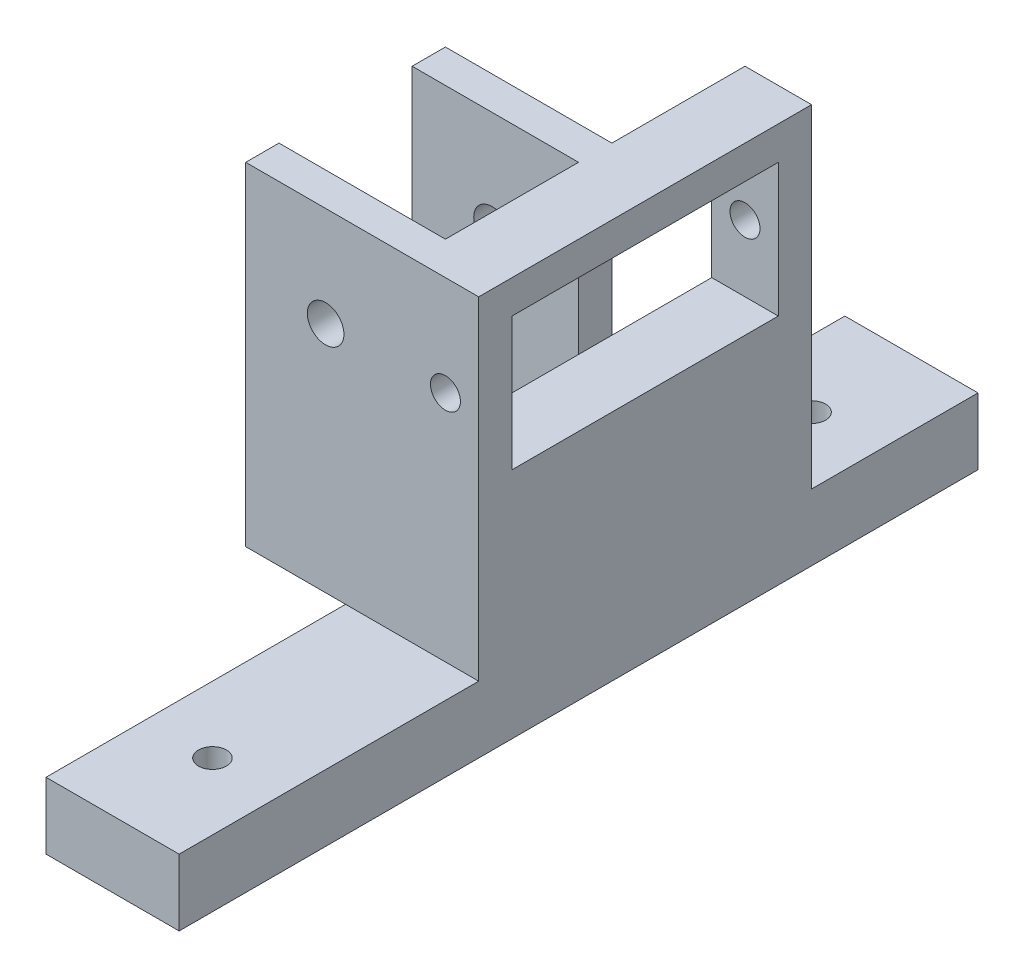
SolidWorks part; units mm, degrees
ref_plane "Front Plane" through (0, 0, 0) normal (0, 0, 1) x (1, 0, 0)
ref_plane "Top Plane" through (0, 0, 0) normal (0, 1, 0) x (1, 0, 0)
ref_plane "Right Plane" through (0, 0, 0) normal (1, 0, 0) x (0, 0, -1)
sketch "Sketch4" plane through (0, 0, 0) normal (0, 1, 0) x (1, 0, 0)
  line L1 (0, 0) -> (40, 0)
  line L2 (0, 0) -> (0, 80)
  line L3 (0, 80) -> (40, 80)
  line L4 (40, 0) -> (40, 80)
  dimension "D1" = 80
  dimension "D2" = 40
extrude "Boss-Extrude4" add sketch "Sketch4" along normal blind 5
sketch "Sketch5" plane through (0, 5, 0) normal (0, 1, 0) x (1, 0, 0)
  line L0 (40, 40) -> (30, 40)
  line L1 (30, 30) -> (30, 50) construction
  line L2 (40, 50) -> (30, 50)
  line L3 (30, 50) -> (30, 55)
  line L4 (0, 80) -> (0, 0)
  line L5 (0, 0) -> (40, 0)
  line L6 (40, 0) -> (40, 80)
  line L7 (40, 80) -> (0, 80)
  line L8 (0, 80) -> (0, 0)
  line L9 (0, 0) -> (40, 0)
  line L10 (40, 0) -> (40, 80)
  line L11 (40, 80) -> (0, 80)
  line L12 (30, 55) -> (40, 55)
  line L13 (40, 55) -> (40, 50)
  line L14 (40, 30) -> (30, 30)
  line L15 (30, 30) -> (30, 25)
  line L16 (30, 25) -> (40, 25)
  line L17 (40, 25) -> (40, 30)
  point P9 (30, 40)
  line M11 (40, 0) -> (40, 80)
  dimension "D2" = 10
  dimension "D3" = 10
  dimension "D4" = 5
  dimension "D5" = 5
  dimension "D1" = 0
extrude "Boss-Extrude6" add sketch "Sketch5" along normal blind 50 contours L12 L3 L2 M11 | L15 L16 L10 L14
sketch "Sketch7" plane through (0, 0, -50) normal (0, 0, 1) x (1, 0, 0)
  line L1 (30, 5) -> (40, 5)
  line L2 (30, 5) -> (30, 30)
  line L3 (30, 30) -> (40, 30)
  line L4 (40, 5) -> (40, 30)
  line L5 (40, 55) -> (40, 5) construction
  line L7 (30, 55) -> (40, 55)
  line L8 (30, 55) -> (30, 50)
  line L9 (30, 50) -> (40, 50)
  line L10 (40, 55) -> (40, 50)
  dimension "D1" = 25
  dimension "D2" = 10
  dimension "D3" = 5
extrude "Boss-Extrude7" add sketch "Sketch7" along normal up to surface (20 mm away) contours L8 L7 L10 L9 | L2 L1 L4 L3 up to face at (35, 30, -30)
sketch "Sketch9" plane through (0, 0, 0) normal (-1, 0, 0) x (0, 0, 1)
  line L4 (-80, 0) -> (0, 0)
  line L5 (0, 0) -> (0, 5)
  line L6 (0, 5) -> (-80, 5)
  line L7 (-80, 5) -> (-80, 0)
  line L8 (-80, 0) -> (0, 0)
  line L9 (0, 0) -> (0, 5)
  line L10 (0, 5) -> (-80, 5)
  line L12 (-80, 5) -> (-80, 0)
  dimension "D1" = 0
extrude "Boss-Extrude9" add sketch "Sketch9" along normal blind 10
sketch "Sketch10" plane through (0, 0, 0) normal (0, 0, 1) x (1, 0, 0)
  line L4 (-10, 0) -> (40, 0)
  line L5 (40, 0) -> (40, 5)
  line L6 (40, 5) -> (-10, 5)
  line L7 (-10, 5) -> (-10, 0)
  line L8 (-10, 0) -> (40, 0)
  line L9 (40, 0) -> (40, 5)
  line L10 (40, 5) -> (-10, 5)
  line L11 (-10, 5) -> (-10, 0)
  dimension "D1" = 0
extrude "Boss-Extrude10" add sketch "Sketch10" along normal blind 20
sketch "Sketch11" plane through (0, 0, -50) normal (0, 0, 1) x (1, 0, 0)
  line L0 (30, 40) -> (35, 40)
  line L4 (30, 30) -> (40, 30)
  line L5 (40, 30) -> (40, 50)
  line L6 (40, 50) -> (30, 50)
  line L7 (30, 50) -> (30, 30)
  line L8 (30, 30) -> (40, 30)
  line L9 (40, 30) -> (40, 50)
  line L10 (40, 50) -> (30, 50)
  line L11 (30, 50) -> (30, 30)
  circle A0 centre (35, 40) radius 2.25
  dimension "D3" = 4.5
  dimension "D2" = 5
  dimension "D1" = 0
extrude "Cut-Extrude1" cut sketch "Sketch11" against normal mid plane 50
sketch "Sketch12" plane through (0, 0, -25) normal (0, 0, 1) x (1, 0, 0)
  circle A0 centre (35, 40) radius 2.25 construction
  circle A1 centre (35, 40) radius 2.25
  circle A2 centre (35, 40) radius 4
  dimension "D1" = 8
extrude "Cut-Extrude2" cut sketch "Sketch12" against normal blind 2
sketch "Sketch15" plane through (30, 0, 0) normal (-1, 0, 0) x (0, 0, 1)
  line L1 (-55, 55) -> (-50, 55)
  line L2 (-55, 55) -> (-55, 5)
  line L3 (-55, 5) -> (-50, 5)
  line L4 (-50, 55) -> (-50, 5)
  line L5 (-25, 55) -> (-30, 55)
  line L6 (-25, 55) -> (-25, 5)
  line L7 (-25, 5) -> (-30, 5)
  line L8 (-30, 55) -> (-30, 5)
  dimension "D1" = 50
  dimension "D2" = 5
  dimension "D3" = 50
  dimension "D4" = 5
extrude "Boss-Extrude11" add sketch "Sketch15" along normal blind 20
sketch "Sketch16" plane through (0, 0, -25) normal (0, 0, 1) x (1, 0, 0)
  line L0 (35, 40) -> (17, 40)
  circle A0 centre (35, 40) radius 4 construction
  circle A1 centre (35, 40) radius 4
  circle A2 centre (17, 40) radius 2.75
  dimension "D2" = 5.5
  dimension "D1" = 18
extrude "Cut-Extrude4" cut sketch "Sketch16" against normal up to surface (30 mm away) up to face at (32.75, 40, -55)
sketch "Sketch19" plane through (10, 0, 0) normal (-1, 0, 0) x (0, 0, 1)
  line L4 (-55, 55) -> (-55, 5)
  line L5 (-55, 5) -> (-50, 5)
  line L6 (-50, 5) -> (-50, 55)
  line L7 (-50, 55) -> (-55, 55)
  line L8 (-55, 55) -> (-55, 5)
  line L10 (-50, 5) -> (-50, 55)
  line L11 (-50, 55) -> (-55, 55)
  line L12 (-25, 5) -> (-25, 55)
  line L13 (-25, 55) -> (-30, 55)
  line L14 (-30, 55) -> (-30, 5)
  line L15 (-30, 5) -> (-25, 5)
  line L16 (-25, 5) -> (-25, 55)
  line L17 (-25, 55) -> (-30, 55)
  line L18 (-30, 55) -> (-30, 5)
  line L20 (-55, 5) -> (-50, 5)
  line L21 (-30, 5) -> (-25, 5)
  dimension "D1" = 0
  dimension "D2" = 0
extrude "Boss-Extrude12" add sketch "Sketch19" along normal blind 5
sketch "Sketch21" plane through (0, 0, 0) normal (0, -1, 0) x (1, 0, 0)
  line L4 (40, -80) -> (40, 20)
  line L5 (40, 20) -> (-10, 20)
  line L6 (-10, 20) -> (-10, -80)
  line L7 (-10, -80) -> (40, -80)
  line L8 (40, -80) -> (40, 20)
  line L9 (40, 20) -> (-10, 20)
  line L10 (-10, 20) -> (-10, -80)
  line L11 (-10, -80) -> (40, -80)
  dimension "D1" = 0
extrude "Boss-Extrude14" add sketch "Sketch21" along normal blind 5
sketch "Sketch22" plane through (0, 0, -80) normal (0, 0, -1) x (-1, 0, 0)
  line L4 (-40, 5) -> (-40, -5)
  line L5 (-40, -5) -> (10, -5)
  line L6 (10, -5) -> (10, 5)
  line L7 (10, 5) -> (-40, 5)
  line L8 (-40, 5) -> (-40, -5)
  line L9 (-40, -5) -> (10, -5)
  line L10 (10, -5) -> (10, 5)
  line L11 (10, 5) -> (-40, 5)
  dimension "D1" = 0
extrude "Boss-Extrude15" add sketch "Sketch22" along normal blind 20
sketch "Sketch24" plane through (0, 55, 0) normal (0, 1, 0) x (1, 0, 0)
  line L1 (5, 55) -> (40, 55)
  line L2 (5, 55) -> (5, 50)
  line L3 (5, 50) -> (40, 50)
  line L4 (40, 55) -> (40, 50)
  line L5 (40, 25) -> (40, 55) construction
  dimension "D1" = 35
  dimension "D2" = 5
extrude "Cut-Extrude5" cut sketch "Sketch24" against normal blind 50
sketch "Sketch25" plane through (0, 0, -50) normal (0, 0, -1) x (-1, 0, 0)
  line L4 (-30, 5) -> (-30, 30)
  line L5 (-30, 30) -> (-40, 30)
  line L6 (-40, 30) -> (-40, 5)
  line L7 (-40, 5) -> (-30, 5)
  line L8 (-30, 5) -> (-30, 30)
  line L9 (-30, 30) -> (-40, 30)
  line L10 (-40, 30) -> (-40, 5)
  line L11 (-40, 5) -> (-30, 5)
  line L12 (-30, 50) -> (-30, 55)
  line L13 (-30, 55) -> (-40, 55)
  line L14 (-40, 55) -> (-40, 50)
  line L15 (-40, 50) -> (-30, 50)
  line L16 (-30, 50) -> (-30, 55)
  line L17 (-30, 55) -> (-40, 55)
  line L18 (-40, 55) -> (-40, 50)
  line L19 (-40, 50) -> (-30, 50)
  dimension "D1" = 0
  dimension "D2" = 0
extrude "Boss-Extrude16" add sketch "Sketch25" along normal blind 25
sketch "Sketch26" plane through (0, 30, 0) normal (0, 1, 0) x (1, 0, 0)
  line L1 (40, 75) -> (30, 75)
  line L2 (40, 75) -> (40, 70)
  line L3 (40, 70) -> (30, 70)
  line L4 (30, 75) -> (30, 70)
  line L5 (30, 30) -> (30, 75) construction
  dimension "D1" = 5
  dimension "D2" = 10
extrude "Boss-Extrude17" add sketch "Sketch26" along normal blind 20
sketch "Sketch27" plane through (0, 0, -27) normal (0, 0, 1) x (1, 0, 0)
  circle A0 centre (35, 40) radius 2.25 construction
  circle A1 centre (35, 40) radius 4
  circle A2 centre (35, 40) radius 4
  circle A3 centre (35, 40) radius 2.25
  dimension "D1" = 0
extrude "Boss-Extrude18" add sketch "Sketch27" along normal up to surface (2 mm away) up to face at (19.75, 40, -25)
sketch "Sketch28" plane through (0, 0, -25) normal (0, 0, 1) x (1, 0, 0)
  circle A0 centre (35, 40) radius 2.25 construction
  circle A1 centre (35, 40) radius 2.25
extrude "Cut-Extrude6" cut sketch "Sketch28" against normal blind 50
sketch "Sketch29" plane through (0, 5, 0) normal (0, 1, 0) x (1, 0, 0)
  line L0 (5, 30) -> (5, 50) construction
  line L2 (5, 50) -> (30, 50)
  line L3 (5, 50) -> (5, 55)
  line L4 (5, 55) -> (30, 55)
  line L5 (30, 50) -> (30, 55)
  line L6 (30, 30) -> (30, 75) construction
  dimension "D1" = 20
  dimension "D2" = 5
  dimension "D3" = 25
extrude "Boss-Extrude19" add sketch "Sketch29" along normal up to surface (50 mm away) contours L3 L2 L5 L4
sketch "Sketch31" plane through (0, 0, -25) normal (0, 0, 1) x (1, 0, 0)
  circle A0 centre (17, 40) radius 2.75 construction
  circle A1 centre (17, 40) radius 2.75
extrude "Cut-Extrude7" cut sketch "Sketch31" against normal blind 30
sketch "Sketch32" plane through (0, 5, 0) normal (0, 1, 0) x (1, 0, 0)
  line L0 (-10, 100) -> (40, 100) construction
  line L1 (20, 100) -> (-10, 100)
  line L2 (20, 100) -> (20, 55)
  line L3 (20, 55) -> (-10, 55)
  line L4 (-10, 100) -> (-10, 55)
  line L5 (20, 480) -> (20, -20) construction
  line L6 (-10, -20) -> (-10, 100) construction
  line L7 (5, 25) -> (40, 25) construction
  line L8 (-10, -20) -> (20, -20)
  line L9 (-10, -20) -> (-10, 25)
  line L10 (-10, 25) -> (20, 25)
  line L11 (20, -20) -> (20, 25)
  dimension "D1" = 45
  dimension "D2" = 30
extrude "Cut-Extrude8" cut sketch "Sketch32" against normal blind 10
sketch "Sketch33" plane through (-10, 0, 0) normal (-1, 0, 0) x (0, 0, 1)
  line L4 (-55, 5) -> (-55, -5)
  line L5 (-55, -5) -> (-25, -5)
  line L6 (-25, -5) -> (-25, 5)
  line L7 (-25, 5) -> (-55, 5)
  line L8 (-55, 5) -> (-55, -5)
  line L9 (-55, -5) -> (-25, -5)
  line L10 (-25, -5) -> (-25, 5)
  line L11 (-25, 5) -> (-55, 5)
  dimension "D1" = 0
extrude "Cut-Extrude9" cut sketch "Sketch33" against normal up to surface (30 mm away) up to face at (20, 0, -2.5)
sketch "Sketch35" plane through (0, 5, 0) normal (0, 1, 0) x (1, 0, 0)
  line L0 (30, -20) -> (30, -5) construction
  line L1 (40, -20) -> (20, -20) construction
  line L2 (30, 100) -> (30, 85) construction
  line L3 (20, 100) -> (40, 100) construction
  circle A0 centre (30, 85) radius 2.1
  circle A1 centre (30, -5) radius 2.1
  dimension "D3" = 4.2
  dimension "D4" = 4.2
  dimension "D1" = 15
  dimension "D2" = 15
extrude "Cut-Extrude10" cut sketch "Sketch35" against normal blind 10
